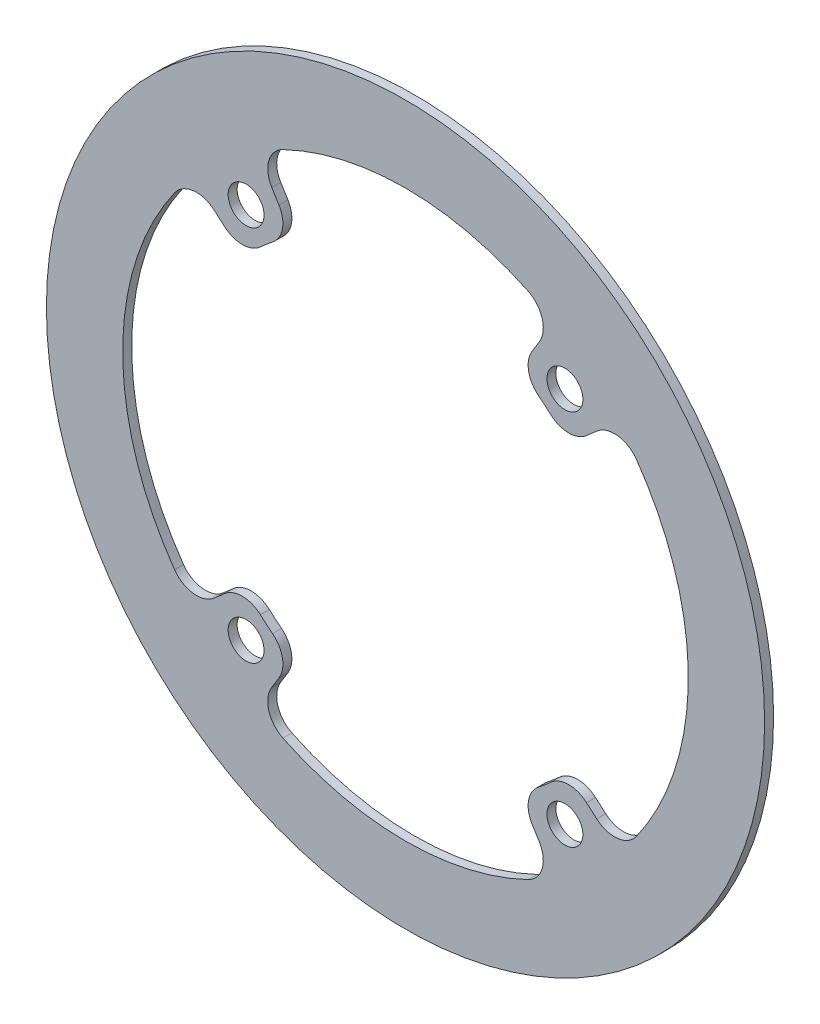
SolidWorks part; units mm, degrees
material "Thornel Mat VMA"
ref_plane "前视基准面" through (0, 0, 0) normal (0, 0, 1) x (1, 0, 0)
ref_plane "上视基准面" through (0, 0, 0) normal (0, 1, 0) x (1, 0, 0)
ref_plane "右视基准面" through (0, 0, 0) normal (1, 0, 0) x (0, 0, -1)
sketch "草图1" plane through (0, 0, 0) normal (0, 0, 1) x (1, 0, 0)
  circle A0 centre (0, 0) radius 40
  circle A1 centre (0, 0) radius 35 construction
  circle A2 centre (0, 0) radius 31 construction
  circle A4 centre (0, 0) radius 24
  dimension "D1" = 80
  dimension "D2" = 70
  dimension "D5" = 48
  dimension "D3" = 4
extrude "凸台-拉伸1" add sketch "草图1" along normal blind 1
sketch "草图2" plane through (0, 0, 1) normal (0, 0, 1) x (1, 0, 0)
  line L0 (17.7553, -21) -> (0, 0) construction
  line L1 (-40, 25) -> (40, 25) construction
  line L2 (-40, 25) -> (-40, -25) construction
  line L3 (-40, -25) -> (40, -25) construction
  line L4 (40, 25) -> (40, -25) construction
  line L5 (-40, 25) -> (40, -25) construction
  line L6 (-40, -25) -> (40, 25) construction
  line L7 (0, 0) -> (43.1743, 0) construction
  line L8 (0, 0) -> (0, 16.6048) construction
  circle A0 centre (0, 0) radius 40 construction
  circle A1 centre (17.7553, -21) radius 2
  circle A2 centre (17.7553, 21) radius 2
  circle A3 centre (-17.7553, -21) radius 2
  circle A4 centre (-17.7553, 21) radius 2
  point P0 (0, 0)
  dimension "D3" = 4
  dimension "D1" = 50
  dimension "D2" = 27.5
  dimension "D4" = 4
extrude "切除-拉伸1" cut sketch "草图2" against normal blind 10
sketch "草图3" plane through (0, 0, 1) normal (0, 0, 1) x (1, 0, 0)
  line L0 (12.6164, -20.4163) -> (16.559, -26.7965)
  line L1 (0, 0) -> (17.7553, -21) construction
  line L2 (18.0343, -15.8356) -> (23.67, -20.7842)
  line L3 (12.6164, -20.4163) -> (0, 0) construction
  line L4 (0, 0) -> (18.0343, -15.8356) construction
  line L5 (17.5746, 0) -> (0, 0) construction
  line L6 (0, 0) -> (0, 12.9447) construction
  line L7 (12.6164, 20.4163) -> (16.559, 26.7965)
  line L8 (18.0343, 15.8356) -> (23.67, 20.7842)
  line L9 (-12.6164, 20.4163) -> (-16.559, 26.7965)
  line L10 (-18.0343, 15.8356) -> (-23.67, 20.7842)
  line L11 (-12.6164, -20.4163) -> (-16.559, -26.7965)
  line L12 (-18.0343, -15.8356) -> (-23.67, -20.7842)
  arc A0 (23.67, -20.7842) -> (23.67, 20.7842) centre (0, 0) ccw
  circle A1 centre (0, 0) radius 24 construction
  arc A2 (18.0343, -15.8356) -> (18.0343, 15.8356) centre (0, 0) ccw
  arc A3 (-16.559, -26.7965) -> (16.559, -26.7965) centre (0, 0) ccw
  arc A4 (-12.6164, -20.4163) -> (12.6164, -20.4163) centre (0, 0) ccw
  arc A5 (-23.67, 20.7842) -> (-23.67, -20.7842) centre (0, 0) ccw
  arc A6 (-18.0343, 15.8356) -> (-18.0343, -15.8356) centre (0, 0) ccw
  arc A7 (12.6164, 20.4163) -> (-12.6164, 20.4163) centre (0, 0) ccw
  arc A8 (16.559, 26.7965) -> (-16.559, 26.7965) centre (0, 0) ccw
  dimension "D1" = 63
  dimension "D2" = 17
extrude "切除-拉伸2" cut sketch "草图3" against normal blind 10
fillet "圆角1" radius 3 16 edges at (-18.0343, -15.8356, 0.5) (-23.67, -20.7842, 0.5) (-23.67, 20.7842, 0.5) (-12.6164, 20.4163, 0.5) (-16.559, 26.7965, 0.5) (16.559, 26.7965, 0.5) (12.6164, 20.4163, 0.5) (18.0343, 15.8356, 0.5) (23.67, 20.7842, 0.5) (23.67, -20.7842, 0.5) (18.0343, -15.8356, 0.5) (12.6164, -20.4163, 0.5) (16.559, -26.7965, 0.5) (-16.559, -26.7965, 0.5) (-12.6164, -20.4163, 0.5) (-18.0343, 15.8356, 0.5)
